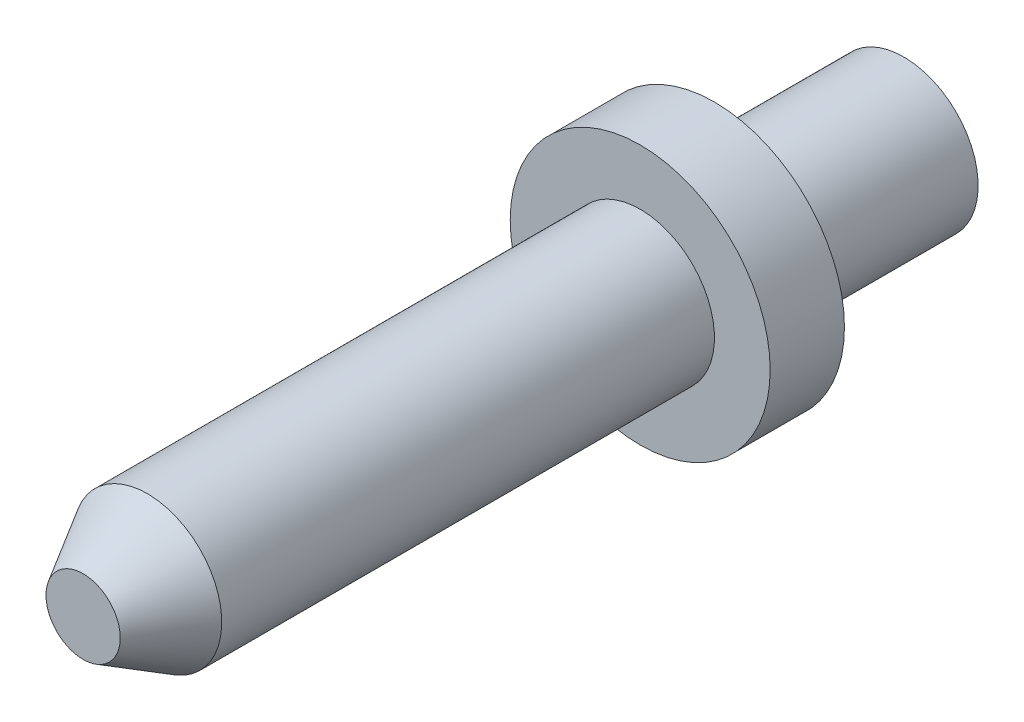
SolidWorks part; units mm, degrees
ref_plane "Front Plane" through (0, 0, 0) normal (0, 0, 1) x (1, 0, 0)
ref_plane "Top Plane" through (0, 0, 0) normal (0, 1, 0) x (1, 0, 0)
ref_plane "Right Plane" through (0, 0, 0) normal (1, 0, 0) x (0, 0, -1)
sketch "Sketch1" plane through (0, 0, 0) normal (0, 1, 0) x (1, 0, 0)
  line L0 (0, 1.7021) -> (0, -2.1079) construction
  line L1 (0, -2.1079) -> (0.508, -2.1079)
  line L3 (0, 1.7021) -> (0.508, 1.7021)
  line L4 (0.508, -2.1079) -> (0.508, 1.7021)
  line L5 (0, 0) -> (0.508, 1.7021) construction
  line L6 (0, 0) -> (0.508, -2.1079) construction
  line L7 (0.3175, 3.5055) -> (0.3175, 2.4895)
  line L8 (0, 1.7021) -> (0.889, 1.7021)
  line L9 (0, 1.7021) -> (0, 2.2101)
  line L10 (0, 2.2101) -> (0.889, 2.2101)
  line L11 (0.889, 1.7021) -> (0.889, 2.2101)
  line L12 (0, 2.2101) -> (0.508, 2.2101)
  line L13 (0, 2.2101) -> (0, 3.5055)
  line L14 (0, 3.5055) -> (0.508, 3.5055)
  line L15 (0.508, 2.2101) -> (0.508, 3.5055)
  line L16 (0.3175, 2.4895) -> (0, 2.3207)
  line L17 (0.508, -1.6679) -> (0.254, -2.1079)
  line L18 (0, 1.7021) -> (0, -2.1079)
  point P0 (0, 0)
  dimension "D1" = 3.81
  dimension "D2" = 0.508
  dimension "D3" = 0.508
  dimension "D4" = 118
  dimension "D5" = 0.3175
  dimension "D6" = 0.889
  dimension "D7" = 0.508
  dimension "D8" = 1.2954
  dimension "D9" = 1.016
  dimension "D10" = 60
  dimension "D11" = 0.254
revolve "Revolve1" add sketch "Sketch1" angle 360 about L18
